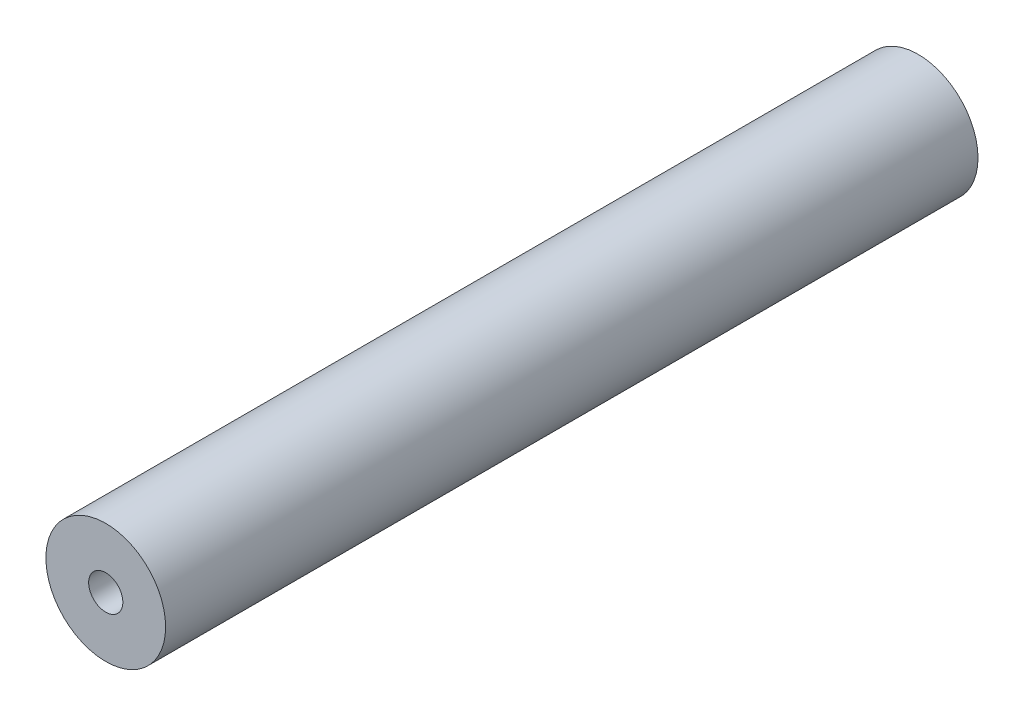
SolidWorks part; units mm, degrees
material "灰铸铁"
ref_plane "前视基准面" through (0, 0, 0) normal (0, 0, 1) x (1, 0, 0)
ref_plane "上视基准面" through (0, 0, 0) normal (0, 1, 0) x (1, 0, 0)
ref_plane "右视基准面" through (0, 0, 0) normal (1, 0, 0) x (0, 0, -1)
sketch "草图1" plane through (0, 0, 0) normal (0, 0, 1) x (1, 0, 0)
  circle A0 centre (0, 0) radius 7
  dimension "D1" = 14
extrude "凸台-拉伸1" add sketch "草图1" along normal blind 95
sketch "草图2" plane through (0, 0, 95) normal (0, 0, 1) x (1, 0, 0)
  circle A0 centre (0, 0) radius 2
  dimension "D1" = 4
extrude "切除-拉伸1" cut sketch "草图2" against normal blind 65 contours A0
